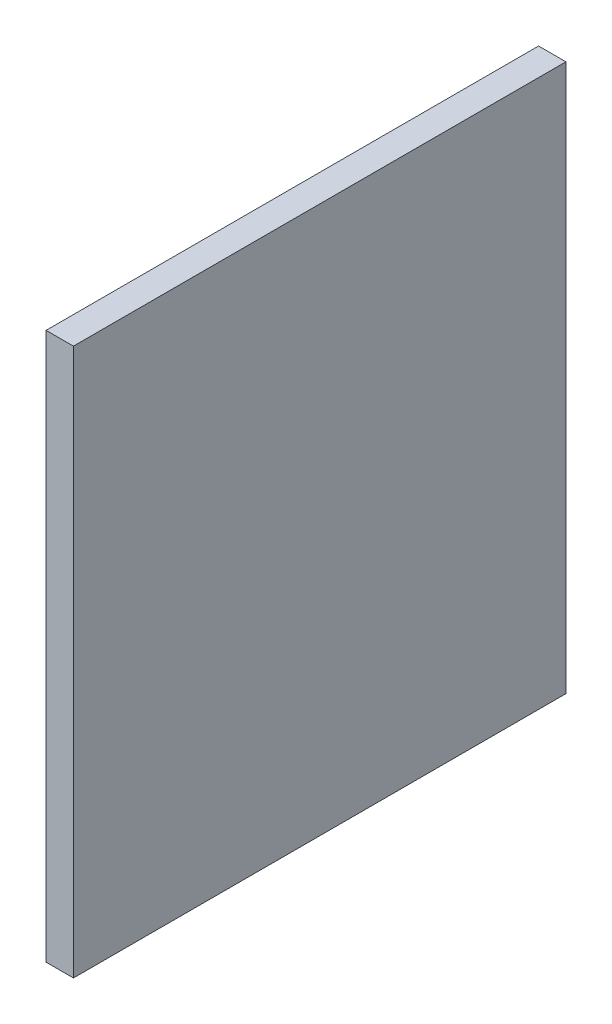
SolidWorks part; units mm, degrees
ref_plane "Front Plane" through (0, 0, 0) normal (0, 0, 1) x (1, 0, 0)
ref_plane "Top Plane" through (0, 0, 0) normal (0, 1, 0) x (1, 0, 0)
ref_plane "Right Plane" through (0, 0, 0) normal (1, 0, 0) x (0, 0, -1)
sketch "Sketch2" plane through (0, 0, 0) normal (1, 0, 0) x (0, 0, -1)
  line L1 (0, 0) -> (330, 0)
  line L2 (0, 0) -> (0, 200)
  line L3 (0, 200) -> (330, 200)
  line L4 (330, 0) -> (330, 200)
extrude "Boss-Extrude1" add sketch "Sketch2" along normal blind 10
sketch "Sketch3" plane through (10, 0, 0) normal (1, 0, 0) x (0, 0, -1)
  circle A0 centre (16, 25) radius 5
extrude "Cut-Extrude1" cut sketch "Sketch3" against normal blind 10
ref_plane "Plane1" through (0, 100, 0) normal (0, 1, 0) x (1, 0, 0)
ref_plane "Plane2" through (0, 50, 0) normal (0, 1, 0) x (1, 0, 0)
mirror "Mirror1" about plane through (0, 50, 0) normal (0, 1, 0) of "Cut-Extrude1"
mirror "Mirror2" about plane through (0, 100, 0) normal (0, 1, 0) of "Mirror1", "Cut-Extrude1"
sketch "Sketch4" plane through (0, 0, 0) normal (0, 0, 1) x (1, 0, 0)
  line L0 (0, 200) -> (0, 0) construction
  line L1 (0, 200) -> (10, 200)
  line L2 (0, 200) -> (0, 0)
  line L3 (0, 0) -> (10, 0)
  line L4 (10, 200) -> (10, 0)
extrude "Cut-Extrude2" cut sketch "Sketch4" against normal blind 150
